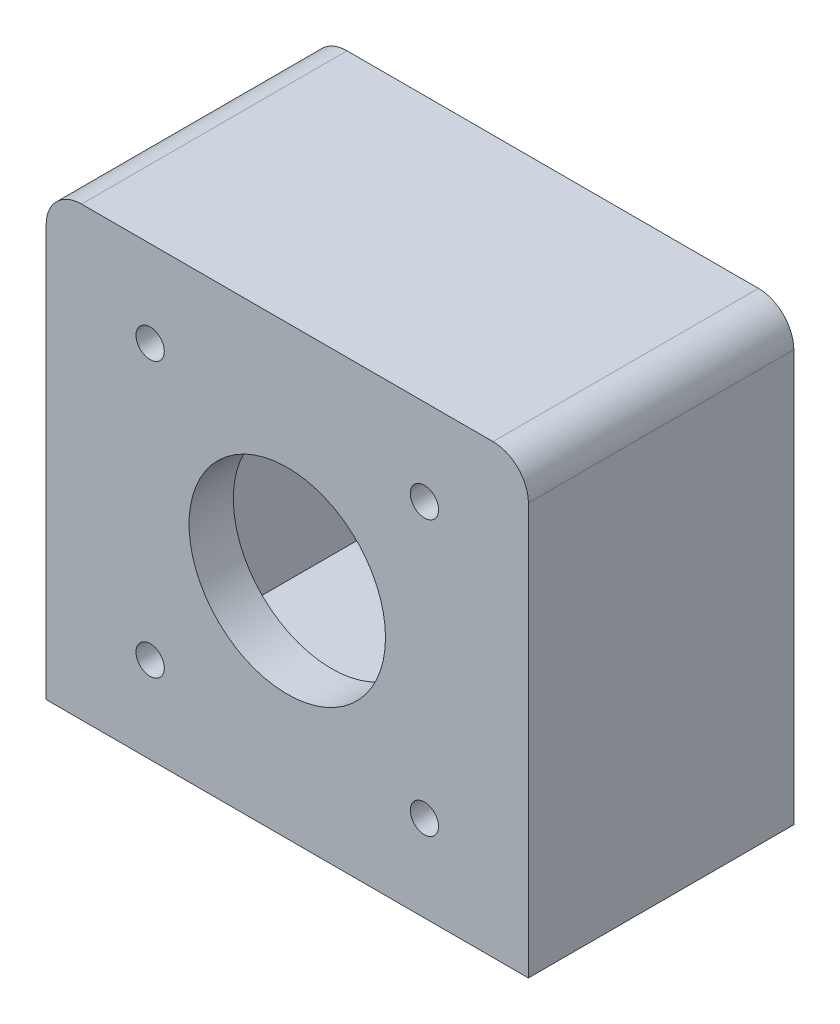
SolidWorks part; units mm, degrees
ref_plane "Front Plane" through (0, 0, 0) normal (0, 0, 1) x (1, 0, 0)
ref_plane "Top Plane" through (0, 0, 0) normal (0, 1, 0) x (1, 0, 0)
ref_plane "Right Plane" through (0, 0, 0) normal (1, 0, 0) x (0, 0, -1)
sketch "Sketch1" plane through (0, 0, 0) normal (0, 0, 1) x (1, 0, 0)
  line L0 (-25.25, -25.25) -> (-25.25, 25.25)
  line L1 (-21.25, -21.25) -> (21.25, -21.25)
  line L2 (-21.25, -21.25) -> (-21.25, 21.25)
  line L3 (-21.25, 21.25) -> (21.25, 21.25)
  line L4 (21.25, -21.25) -> (21.25, 21.25)
  line L5 (-21.25, -21.25) -> (21.25, 21.25) construction
  line L6 (-21.25, 21.25) -> (21.25, -21.25) construction
  line L7 (-25.25, 25.25) -> (25.25, 25.25)
  line L8 (25.25, -25.25) -> (25.25, 25.25)
  line L9 (-25.25, -25.25) -> (25.25, -25.25)
  point P0 (0, 0)
  dimension "D1" = 42.5
  dimension "D2" = 42.5
  dimension "D3" = 4
extrude "Boss-Extrude1" add sketch "Sketch1" along normal blind 25
ref_plane "Plane1" through (0, 0, 25) normal (0, 0, 1) x (1, 0, 0)
sketch "Sketch3" plane through (0, 0, 25) normal (0, 0, 1) x (1, 0, 0)
  line L0 (-15.5, 0) -> (15.5, 0) construction
  line L3 (0, 13.5) -> (0, -13.5)
  line L4 (-15.5, 0) -> (-15.5, 15.5) construction
  line L7 (-25.25, 25.25) -> (25.25, 25.25)
  line L8 (-25.25, 25.25) -> (-25.25, -25.25)
  line L9 (-25.25, -25.25) -> (25.25, -25.25)
  line L10 (25.25, 25.25) -> (25.25, -25.25)
  circle A0 centre (0, 0) radius 11.1
  circle A1 centre (-15.5, 15.5) radius 1.6
  circle A5 centre (15.5, 15.5) radius 1.6
  circle A6 centre (15.5, -15.5) radius 1.6
  circle A7 centre (-15.5, -15.5) radius 1.6
  point P9 (0, 0)
  dimension "D1" = 15.5
extrude "Boss-Extrude2" add sketch "Sketch3" along normal blind 5
ref_plane "Plane3" through (0, -27.3, 0) normal (0, -1, 0) x (-1, 0, 0)
ref_plane "Plane4" through (-25.25, 0, 0) normal (-1, 0, 0) x (0, 0, 1)
sketch "Sketch6" plane through (-25.25, 0, 0) normal (-1, 0, 0) x (0, 0, 1)
  line L1 (0, 25.25) -> (30, 25.25)
  line L2 (0, 25.25) -> (0, -25.25)
  line L3 (0, -25.25) -> (30, -25.25)
  line L4 (30, 25.25) -> (30, -25.25)
extrude "Boss-Extrude3" add sketch "Sketch6" along normal blind 2
ref_plane "Plane5" through (25.25, 0, 0) normal (1, 0, 0) x (0, 0, -1)
sketch "Sketch7" plane through (25.25, 0, 0) normal (1, 0, 0) x (0, 0, -1)
  line L1 (-30, 25.25) -> (0, 25.25)
  line L2 (-30, 25.25) -> (-30, -25.25)
  line L3 (-30, -25.25) -> (0, -25.25)
  line L4 (0, 25.25) -> (0, -25.25)
extrude "Boss-Extrude4" add sketch "Sketch7" along normal blind 2
sketch "Sketch5" plane through (0, -27.3, 0) normal (0, -1, 0) x (-1, 0, 0)
  line L0 (-25.25, -3) -> (-24.25, -3) construction
  line L1 (-25.25, -30) -> (-25.25, 0) construction
  line L2 (-24.25, 0) -> (-24.25, -3) construction
  line L3 (27.25, 0) -> (-27.25, 0) construction
  line L4 (0, 0) -> (0, -30) construction
  line L5 (27.25, -30) -> (-27.25, -30) construction
  line L6 (-25.25, -15) -> (25.25, -15) construction
  line L7 (25.25, -30) -> (25.25, 0) construction
  circle A0 centre (-24.25, -3) radius 1.95
  circle A1 centre (24.25, -3) radius 1.95
  circle A2 centre (24.25, -27) radius 1.95
  circle A3 centre (-24.25, -27) radius 1.95
extrude "Cut-Extrude1" cut sketch "Sketch5" against normal blind 5.7
sketch "Sketch8" plane through (0, 0, 0) normal (0, 0, -1) x (-1, 0, 0)
  line L0 (-21.25, -21.25) -> (-21.25, 21.25) construction
  line L3 (-23.25, 25.25) -> (-21.25, 25.25)
  line L5 (-27.25, 21.25) -> (-27.25, 16.2895)
  line L6 (-27.25, 16.2895) -> (-21.25, 16.2895)
  line L7 (-21.25, 25.25) -> (-21.25, 16.2895)
  line L8 (0, 0) -> (0, 21.25) construction
  line L9 (-21.25, 21.25) -> (21.25, 21.25) construction
  line L10 (27.25, 16.2895) -> (21.25, 16.2895)
  line L11 (21.25, 25.25) -> (21.25, 16.2895)
  line L12 (23.25, 25.25) -> (21.25, 25.25)
  line L13 (27.25, 21.25) -> (27.25, 16.2895)
  line L14 (27.25, 21.25) -> (27.25, 25.25)
  line L15 (27.25, 25.25) -> (21.25, 25.25)
  line L16 (-27.25, 21.25) -> (-27.25, 25.25)
  line L17 (-27.25, 25.25) -> (-21.25, 25.25)
  arc A0 (-23.25, 25.25) -> (-27.25, 21.25) centre (-23.25, 21.25) ccw
  arc A1 (23.25, 25.25) -> (27.25, 21.25) centre (23.25, 21.25) cw
  point P10 (-27.25, 25.25)
  line M16 (27.25, -25.25) -> (27.25, 25.25)
  line M17 (27.25, 25.25) -> (-27.25, 25.25)
  line M18 (-27.25, 25.25) -> (-27.25, -25.25)
  dimension "D1" = 4
extrude "Cut-Extrude2" cut sketch "Sketch8" against normal through all contours A1 M17 M16 | A0 M17 M18
